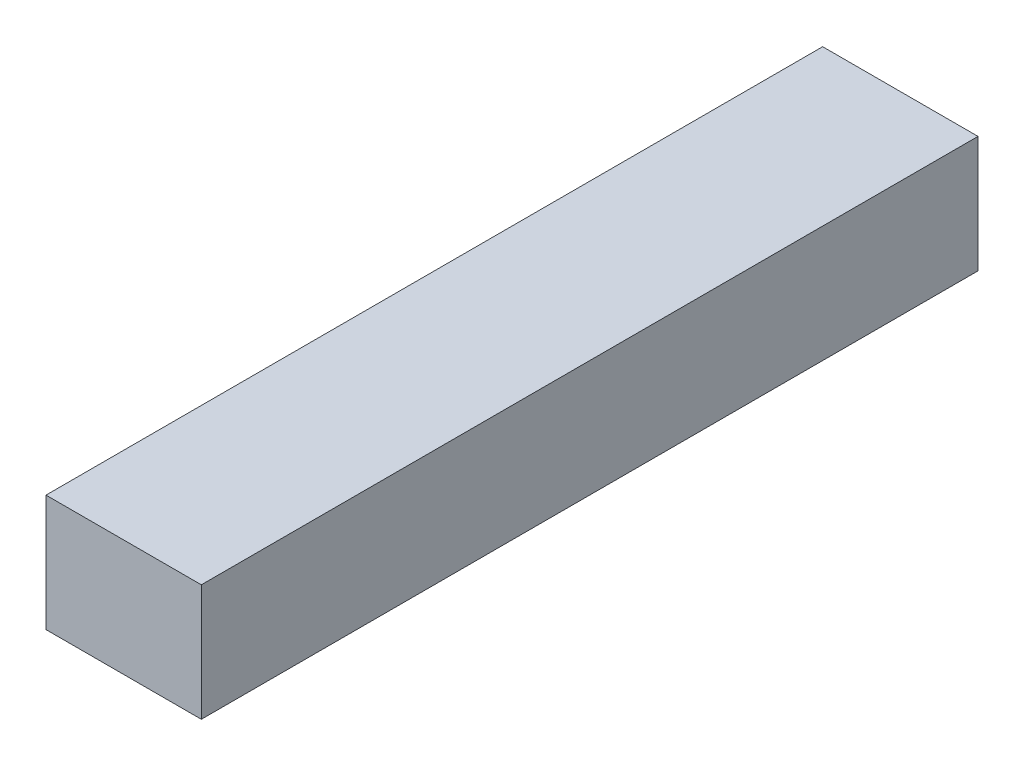
SolidWorks part; units mm, degrees
ref_plane "前视基准面" through (0, 0, 0) normal (0, 0, 1) x (1, 0, 0)
ref_plane "上视基准面" through (0, 0, 0) normal (0, 1, 0) x (1, 0, 0)
ref_plane "右视基准面" through (0, 0, 0) normal (1, 0, 0) x (0, 0, -1)
other "Configuration Table"
sketch "草图1" plane through (0, 0, 0) normal (0, 1, 0) x (1, 0, 0)
  line L1 (-10, 100) -> (10, 100)
  line L2 (-10, 100) -> (-10, 0)
  line L3 (-10, 0) -> (10, 0)
  line L4 (10, 100) -> (10, 0)
  point P4 (0, 0)
  dimension "D1" = 20
  dimension "D2" = 100
extrude "凸台-拉伸1" add sketch "草图1" along normal blind 15
